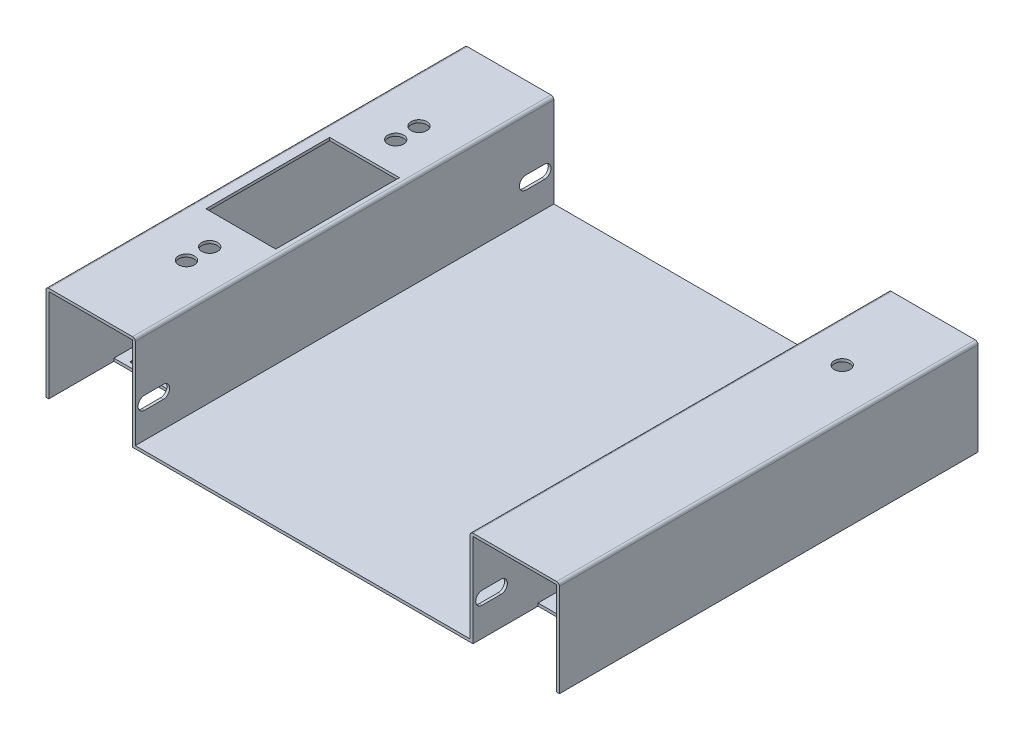
SolidWorks part; units mm, degrees
ref_plane "Front Plane" through (0, 0, 0) normal (0, 0, 1) x (1, 0, 0)
ref_plane "Top Plane" through (0, 0, 0) normal (0, 1, 0) x (1, 0, 0)
ref_plane "Right Plane" through (0, 0, 0) normal (1, 0, 0) x (0, 0, -1)
ref_plane "Plane1" through (0, 120.173, 0) normal (0, 1, 0) x (1, 0, 0)
sketch "Sketch1" plane through (0, 120.173, 0) normal (0, 1, 0) x (1, 0, 0)
  line L0 (-276, 0) -> (-276, -450)
  line L1 (-276, -450) -> (276, -450)
  line L2 (276, -450) -> (276, 0)
  line L3 (276, 0) -> (-276, 0)
extrude "Boss-Extrude1" add sketch "Sketch1" against normal blind 100
ref_plane "Plane2" through (-273, 0, 0) normal (-1, 0, 0) x (0, -1, 0)
sketch "Sketch2" plane through (-273, 0, 0) normal (-1, 0, 0) x (0, -1, 0)
  line L0 (-117.173, 0) -> (-20.173, 0)
  line L1 (-20.173, 0) -> (-20.173, 450)
  line L2 (-20.173, 450) -> (-117.173, 450)
  line L3 (-117.173, 450) -> (-117.173, 0)
extrude "Cut-Extrude1" cut sketch "Sketch2" against normal blind 90
ref_plane "Plane3" through (273, 0, 0) normal (1, 0, 0) x (0, 0, -1)
sketch "Sketch3" plane through (273, 0, 0) normal (1, 0, 0) x (0, 0, -1)
  line L0 (-450, 117.173) -> (-450, 20.173)
  line L1 (-450, 20.173) -> (0, 20.173)
  line L2 (0, 20.173) -> (0, 117.173)
  line L3 (0, 117.173) -> (-450, 117.173)
extrude "Cut-Extrude2" cut sketch "Sketch3" against normal blind 90
sketch "Sketch4" plane through (0, 20.173, 0) normal (0, -1, 0) x (1, 0, 0)
  line L0 (-273, 360) -> (-273, 0)
  line L1 (-273, 0) -> (-276, 0)
  line L2 (-276, 0) -> (-276, 450)
  line L3 (-276, 450) -> (-273, 450)
  line L4 (-273, 450) -> (-273, 380)
  line L5 (-273, 380) -> (-183, 380)
  line L6 (-183, 380) -> (-183, 450)
  line L7 (-183, 450) -> (183, 450)
  line L8 (183, 450) -> (183, 90)
  line L9 (183, 90) -> (273, 90)
  line L10 (273, 90) -> (273, 450)
  line L11 (273, 450) -> (276, 450)
  line L12 (276, 450) -> (276, 0)
  line L13 (276, 0) -> (273, 0)
  line L14 (273, 0) -> (273, 70)
  line L15 (273, 70) -> (183, 70)
  line L16 (183, 70) -> (183, 0)
  line L17 (183, 0) -> (-183, 0)
  line L18 (-183, 0) -> (-183, 360)
  line L19 (-183, 360) -> (-273, 360)
extrude "Boss-Extrude2" add sketch "Sketch4" along normal blind 3
sketch "Sketch5" plane through (0, 0, 0) normal (0, 0, -1) x (-1, 0, 0)
  line L0 (180, 120.173) -> (-180, 120.173)
  line L1 (-180, 120.173) -> (-180, 20.173)
  line L2 (-180, 20.173) -> (180, 20.173)
  line L3 (180, 20.173) -> (180, 120.173)
extrude "Cut-Extrude3" cut sketch "Sketch5" against normal through all
sketch "Sketch6" plane through (-273, 0, 0) normal (1, 0, 0) x (0, 0, -1)
  line L0 (-70, 17.173) -> (-90, 17.173)
  line L1 (-90, 17.173) -> (-90, 20.173)
  line L2 (-90, 20.173) -> (-70, 20.173)
  line L3 (-70, 20.173) -> (-70, 17.173)
extrude "Boss-Extrude3" add sketch "Sketch6" along normal blind 90
sketch "Sketch7" plane through (273, 0, 0) normal (-1, 0, 0) x (0, 0, 1)
  line L0 (380, 17.173) -> (360, 17.173)
  line L1 (360, 17.173) -> (360, 20.173)
  line L2 (360, 20.173) -> (380, 20.173)
  line L3 (380, 20.173) -> (380, 17.173)
extrude "Boss-Extrude4" add sketch "Sketch7" along normal blind 90
sketch "Sketch8" plane through (-180, 0, 0) normal (1, 0, 0) x (0, 0, -1)
  line L0 (-440, 48.173) -> (-420, 48.173)
  line L1 (-420, 62.173) -> (-440, 62.173)
  arc A0 (-440, 62.173) -> (-440, 48.173) centre (-440, 55.173) ccw
  arc A1 (-420, 48.173) -> (-420, 62.173) centre (-420, 55.173) ccw
extrude "Cut-Extrude4" cut sketch "Sketch8" against normal up to next
sketch "Sketch9" plane through (0, 117.173, 0) normal (0, -1, 0) x (1, 0, 0)
  line L0 (-187.5, 291.5) -> (-262.5, 291.5)
  line L1 (-262.5, 291.5) -> (-262.5, 158.5)
  line L2 (-262.5, 158.5) -> (-187.5, 158.5)
  line L3 (-187.5, 158.5) -> (-187.5, 291.5)
extrude "Cut-Extrude5" cut sketch "Sketch9" against normal through all
sketch "Sketch10" plane through (-183, 0, 0) normal (-1, 0, 0) x (0, 0, 1)
  line L0 (10, 48.173) -> (30, 48.173)
  line L1 (30, 62.173) -> (10, 62.173)
  arc A0 (10, 62.173) -> (10, 48.173) centre (10, 55.173) ccw
  arc A1 (30, 48.173) -> (30, 62.173) centre (30, 55.173) ccw
extrude "Cut-Extrude6" cut sketch "Sketch10" against normal up to next
sketch "Sketch11" plane through (180, 0, 0) normal (-1, 0, 0) x (0, 0, 1)
  line L0 (440, 62.173) -> (420, 62.173)
  line L1 (420, 48.173) -> (440, 48.173)
  arc A0 (440, 48.173) -> (440, 62.173) centre (440, 55.173) ccw
  arc A1 (420, 62.173) -> (420, 48.173) centre (420, 55.173) ccw
extrude "Cut-Extrude7" cut sketch "Sketch11" against normal up to next
sketch "Sketch12" plane through (183, 0, 0) normal (1, 0, 0) x (0, 0, -1)
  line L0 (-10, 62.173) -> (-30, 62.173)
  line L1 (-30, 48.173) -> (-10, 48.173)
  arc A0 (-10, 48.173) -> (-10, 62.173) centre (-10, 55.173) ccw
  arc A1 (-30, 62.173) -> (-30, 48.173) centre (-30, 55.173) ccw
extrude "Cut-Extrude8" cut sketch "Sketch12" against normal up to next
sketch "Sketch13" plane through (0, 20.173, 0) normal (0, 1, 0) x (-1, 0, 0)
  line L0 (261, 85) -> (205, 85)
  line L1 (205, 85) -> (205, 75)
  line L2 (205, 75) -> (261, 75)
  line L3 (261, 75) -> (261, 85)
extrude "Cut-Extrude9" cut sketch "Sketch13" against normal blind 1
sketch "Sketch14" plane through (0, 20.173, 0) normal (0, 1, 0) x (-1, 0, 0)
  line L0 (261, 375) -> (205, 375)
  line L1 (205, 375) -> (205, 365)
  line L2 (205, 365) -> (261, 365)
  line L3 (261, 365) -> (261, 375)
extrude "Cut-Extrude10" cut sketch "Sketch14" against normal blind 1
sketch "Sketch15" plane through (0, 20.173, 0) normal (0, 1, 0) x (-1, 0, 0)
  line L0 (-205, 375) -> (-261, 375)
  line L1 (-261, 375) -> (-261, 365)
  line L2 (-261, 365) -> (-205, 365)
  line L3 (-205, 365) -> (-205, 375)
extrude "Cut-Extrude11" cut sketch "Sketch15" against normal blind 1
sketch "Sketch16" plane through (0, 20.173, 0) normal (0, 1, 0) x (-1, 0, 0)
  line L0 (-205, 85) -> (-261, 85)
  line L1 (-261, 85) -> (-261, 75)
  line L2 (-261, 75) -> (-205, 75)
  line L3 (-205, 75) -> (-205, 85)
extrude "Cut-Extrude12" cut sketch "Sketch16" against normal blind 1
hole_wizard "Ø3.3 (3.3) Diameter Hole1" positions "Sketch18" profile "Sketch17" hole size "Ø3.3" standard "ANSI Metric"
sketch "Sketch18" plane through (0, 19.173, 0) normal (0, 1, 0) x (1, 0, 0)
  point P0 (-254.5, -80)
  point P1 (-211.5, -80)
  point P2 (-254.5, -370)
  point P3 (-211.5, -370)
  point P4 (211.5, -370)
  point P5 (254.5, -370)
  point P6 (211.5, -80)
  point P7 (254.5, -80)
sketch "Sketch17" plane through (-254.5, 19.173, 80) normal (1, 0, 0) x (0, 0, 1)
  line L0 (0, 0) -> (0, 2)
  line L1 (0, 2) -> (1.65, 2)
  line L2 (1.65, 2) -> (1.65, 0)
  line L5 (1.65, 0) -> (0, 0)
  line L11 (0, -6.35) -> (0, 107.95) construction
  dimension "Thru Hole Dia." = 3.3
  dimension "Thru Hole Depth" = 2
hole_wizard "Ø17.0 (17) Diameter Hole1" positions "Sketch20" profile "Sketch19" hole size "Ø17.0" standard "ANSI Metric"
sketch "Sketch20" plane through (0, 120.173, 0) normal (0, 1, 0) x (1, 0, 0)
  point P0 (225, -95)
sketch "Sketch19" plane through (225, 120.173, 95) normal (1, 0, 0) x (0, 0, 1)
  line L0 (0, 0) -> (0, 3)
  line L1 (0, 3) -> (8.5, 3)
  line L2 (8.5, 3) -> (8.5, 0)
  line L5 (8.5, 0) -> (0, 0)
  line L11 (0, -6.35) -> (0, 107.95) construction
  dimension "Thru Hole Dia." = 17
  dimension "Thru Hole Depth" = 3
hole_wizard "Ø17.0 (17) Diameter Hole2" positions "Sketch22" profile "Sketch21" hole size "Ø17.0" standard "ANSI Metric"
sketch "Sketch22" plane through (0, 120.173, 0) normal (0, 1, 0) x (1, 0, 0)
  point P0 (-225, -100)
  point P1 (-225, -125)
  point P2 (-225, -325)
  point P3 (-225, -350)
sketch "Sketch21" plane through (-225, 120.173, 100) normal (1, 0, 0) x (0, 0, 1)
  line L0 (0, 0) -> (0, 103)
  line L1 (0, 103) -> (8.5, 103)
  line L2 (8.5, 103) -> (8.5, 0)
  line L5 (8.5, 0) -> (0, 0)
  line L11 (0, -6.35) -> (0, 107.95) construction
  dimension "Thru Hole Dia." = 17
  dimension "Thru Hole Depth" = 103
fillet "Fillet1" radius 3 4 edges at (276, 120.173, 225) (180, 120.173, 225) (-180, 120.173, 225) (-276, 120.173, 225)
